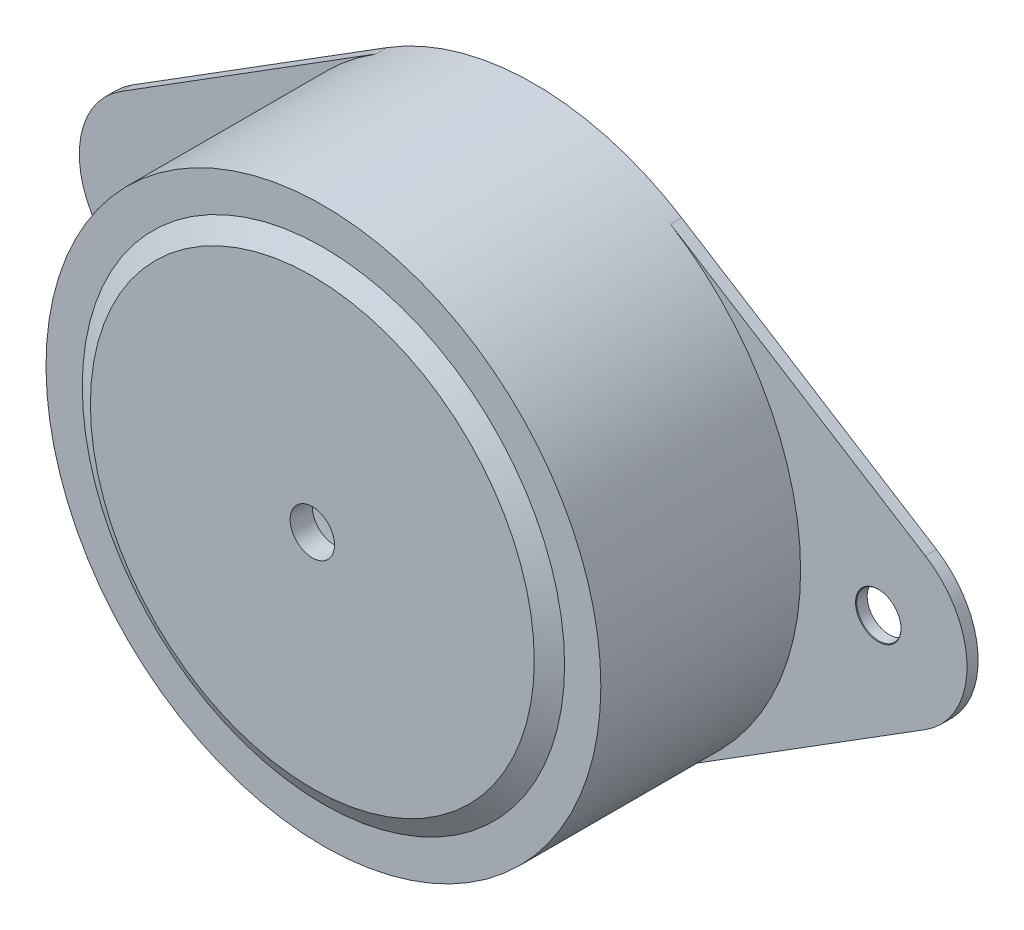
SolidWorks part; units mm, degrees
ref_plane "Plan de face" through (0, 0, 0) normal (0, 0, 1) x (1, 0, 0)
ref_plane "Plan de dessus" through (0, 0, 0) normal (0, 1, 0) x (1, 0, 0)
ref_plane "Plan de droite" through (0, 0, 0) normal (1, 0, 0) x (0, 0, -1)
sketch "Esquisse1" plane through (0, 0, 0) normal (0, 0, 1) x (1, 0, 0)
  line L0 (-61.5685, 0) -> (67.7685, 0) construction
  line L1 (-18.125, 3.3889) -> (-6.6406, 10.5902)
  line L2 (0, -18.7497) -> (0, 18.7497) construction
  line L3 (18.125, 3.3889) -> (6.6406, 10.5902)
  line L4 (18.125, -3.3889) -> (6.6406, -10.5902)
  line L5 (-18.125, -3.3889) -> (-6.6406, -10.5902)
  arc A0 (6.6406, 10.5902) -> (-6.6406, 10.5902) centre (0, 0) ccw
  arc A1 (-18.125, 3.3889) -> (-18.125, -3.3889) centre (-16, 0) ccw
  arc A3 (18.125, 3.3889) -> (18.125, -3.3889) centre (16, 0) cw
  arc A4 (6.6406, -10.5902) -> (-6.6406, -10.5902) centre (0, 0) cw
  dimension "D1" = 25
  dimension "D3" = 8
  dimension "D2" = 16
extrude "Boss.-Extru.1" add sketch "Esquisse1" along normal blind 0.5
sketch "Esquisse2" plane through (0, 0, 0.5) normal (0, 0, 1) x (1, 0, 0)
  circle A0 centre (0, 0) radius 12.5
extrude "Boss.-Extru.2" add sketch "Esquisse2" along normal blind 9
sketch "Esquisse3" plane through (0, 0, 0) normal (1, 0, 0) x (0, 0, -1)
  line L0 (-2.0552, 0) -> (-17.1553, 0) construction
  line L1 (-9.5, 10.866) -> (-10, 10)
  line L2 (-9.5, 12.5) -> (-9.5, -12.5) construction
  line L3 (-10, 10) -> (-10, 0)
  line L4 (-10, 0) -> (-9.5, 0)
  line L5 (-9.5, 0) -> (-9.5, 10.866)
  dimension "D1" = 0.5
  dimension "D2" = 30
  dimension "D3" = 10
revolve "Révolution1" add sketch "Esquisse3" angle 360 about L0
sketch "Esquisse4" plane through (0, 0, 10) normal (0, 0, 1) x (1, 0, 0)
  circle A0 centre (0, 0) radius 1
  dimension "D1" = 2
extrude "Enlèv. mat.-Extru.1" cut sketch "Esquisse4" against normal through all
hole_wizard "Trou taraudé M21" positions "Esquisse3D1" profile "Esquisse6" tap size "M2" standard "ISO"
sketch3d "Esquisse3D1"
  line L0 (16, 0, 0.5) -> (16, 0, 0) construction
  line L1 (-16, 0, 0.5) -> (-16, 0, 0) construction
  point P0 (16, 0, 0.5)
  point P4 (-16, 0, 0.5)
sketch "Esquisse6" plane through (16, 0, 0.5) normal (1, 0, 0) x (0, -1, 0)
  line L0 (0, 0) -> (0, 6.4807)
  line L1 (0, 6.4807) -> (0.8, 6)
  line L2 (0.8, 6) -> (0.8, 4)
  line L3 (0.8, 4) -> (1, 4)
  line L5 (1, 4) -> (1, 0.025)
  line L6 (1, 0.025) -> (1.025, 0)
  line L7 (1.025, 0) -> (0, 0)
  line L8 (-1, 0.025) -> (-1.025, 0) construction
  line L10 (0, 6.4807) -> (-0.8, 6) construction
  line L11 (0, -6.35) -> (0, 107.95) construction
  dimension "Diamètre du trou pour taraudage" = 1.6
  dimension "Profondeur du trou pour taraudage" = 6
  dimension "Diamètre principal du filetage" = 2
  dimension "Profondeur du filetage" = 4
  dimension "Diamètre du fraisage entrant" = 2.05
  dimension "Angle du fraisage entrant" = 90
  dimension "Angle de pointe" = 118
sketch "Esquisse7" plane through (0, 0, 0) normal (0, 0, -1) x (-1, 0, 0)
  circle A0 centre (0, 0) radius 12
  arc A1 (6.6406, 10.5902) -> (-6.6406, 10.5902) centre (0, 0) ccw construction
  dimension "D1" = 0.5
extrude "Enlèv. mat.-Extru.2" cut sketch "Esquisse7" against normal blind 9
sketch "Esquisse8" plane through (0, 0, 0) normal (0, 0, -1) x (-1, 0, 0)
  circle A0 centre (0, 0) radius 12 construction
  circle A1 centre (0, 0) radius 12
  circle A2 centre (0, 0) radius 1 construction
  circle A3 centre (0, 0) radius 1
extrude "Boss.-Extru.3" add sketch "Esquisse8" against normal blind 0.5
